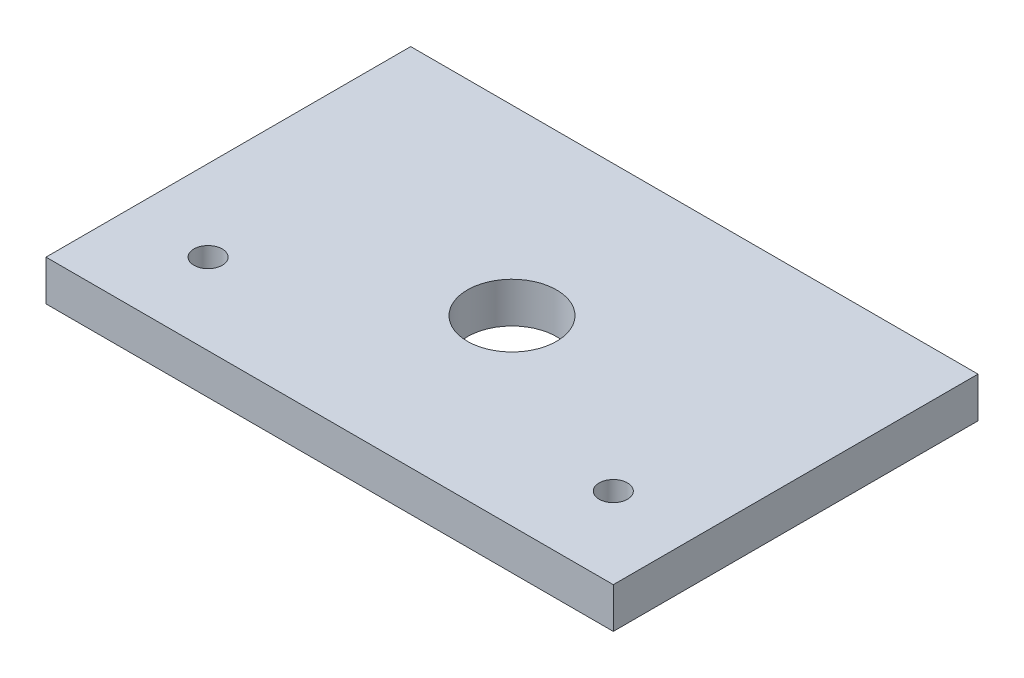
SolidWorks part; units mm, degrees
ref_plane "Front Plane" through (0, 0, 0) normal (0, 0, 1) x (1, 0, 0)
ref_plane "Top Plane" through (0, 0, 0) normal (0, 1, 0) x (1, 0, 0)
ref_plane "Right Plane" through (0, 0, 0) normal (1, 0, 0) x (0, 0, -1)
other "Configuration Table"
sketch "草图1" plane through (0, 0, 0) normal (0, 1, 0) x (1, 0, 0)
  line L1 (-70, -45) -> (70, -45)
  line L2 (-70, -45) -> (-70, 45)
  line L3 (-70, 45) -> (70, 45)
  line L4 (70, -45) -> (70, 45)
  line L5 (-70, -45) -> (70, 45) construction
  line L6 (-70, 45) -> (70, -45) construction
  circle A0 centre (0, 0) radius 11
  circle A1 centre (-50, -25) radius 3.5
  circle A2 centre (50, -25) radius 3.5
  point P0 (0, 0)
extrude "凸台-拉伸1" add sketch "草图1" along normal blind 10
